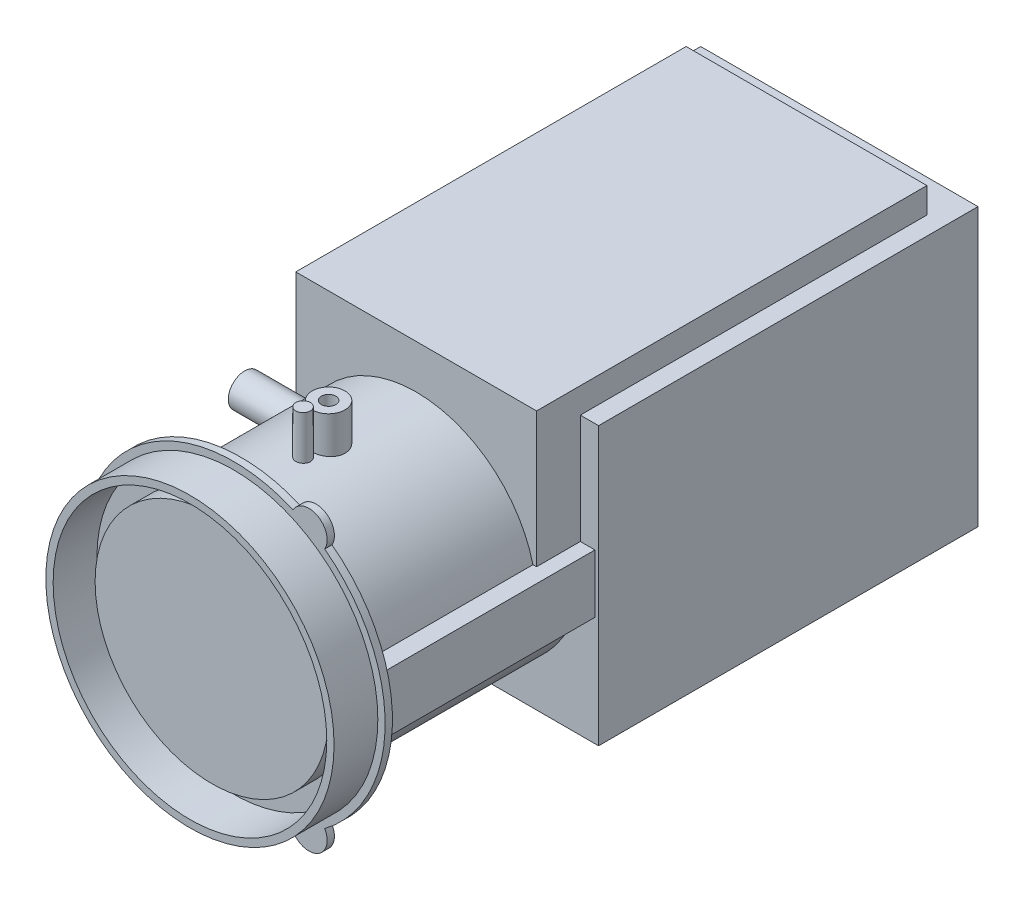
SolidWorks part; units mm, degrees
ref_plane "Front Plane" through (0, 0, 0) normal (0, 0, 1) x (1, 0, 0)
ref_plane "Top Plane" through (0, 0, 0) normal (0, 1, 0) x (1, 0, 0)
ref_plane "Right Plane" through (0, 0, 0) normal (1, 0, 0) x (0, 0, -1)
sketch "Sketch1" plane through (0, 0, 0) normal (0, 0, 1) x (1, 0, 0)
  circle A0 centre (0, 0) radius 19.75
  circle A1 centre (0, 0) radius 18.75
  dimension "D1" = 39.5
  dimension "D2" = 1
extrude "Boss-Extrude1" add sketch "Sketch1" along normal blind 6
sketch "Sketch2" plane through (0, 0, 0) normal (0, 0, -1) x (-1, 0, 0)
  arc A0 (-12.4645, 16.5891) -> (-12.4645, -16.5891) centre (0, 0) ccw
  arc A1 (20.5988, 2.5) -> (20.5988, -2.5) centre (20.5988, 0) cw
  arc A2 (-8.1344, -19.0891) -> (-12.4645, -16.5891) centre (-10.2994, -17.8391) cw
  arc A3 (-12.4645, 16.5891) -> (-8.1344, 19.0891) centre (-10.2994, 17.8391) cw
  arc A4 (20.5988, 2.5) -> (-8.1344, 19.0891) centre (0, 0) ccw
  arc A5 (-8.1344, -19.0891) -> (20.5988, -2.5) centre (0, 0) ccw
  point P7 (-14.3409, 19.3572)
  point P8 (-8.8874, 18.7504)
  point P14 (0, 0)
  point P15 (-12.1037, 16.8542)
  dimension "D1" = 41.5
  dimension "D2" = 2.5
  dimension "D3" = 3
extrude "Boss-Extrude2" add sketch "Sketch2" along normal blind 1
sketch "Sketch3" plane through (0, 0, -1) normal (0, 0, -1) x (-1, 0, 0)
  line L0 (16.0078, 4) -> (18.5, 4)
  line L1 (-18.5, 4) -> (-16.0078, 4)
  line L2 (-18.5, 4) -> (-18.5, -4)
  line L3 (-18.5, -4) -> (-16.0078, -4)
  line L4 (18.5, 4) -> (18.5, -4)
  line L5 (16.0078, -4) -> (18.5, -4)
  arc A0 (-16.0078, -4) -> (16.0078, -4) centre (0, 0) ccw
  arc A1 (16.0078, 4) -> (-16.0078, 4) centre (0, 0) ccw
  point P7 (24.1537, -6.3031)
  point P8 (-18.5, 0)
  dimension "D1" = 33
  dimension "D2" = 8
  dimension "D3" = 37
  dimension "D4" = 18.5
extrude "Boss-Extrude3" add sketch "Sketch3" along normal blind 70
sketch "Sketch4" plane through (0, 0, 0) normal (0, 1, 0) x (1, 0, 0)
  circle A0 centre (0, 13) radius 2.25
  circle A1 centre (0, 13) radius 1
  circle A2 centre (-3, 50.5) radius 2.25 construction
  circle A3 centre (-3, 50.5) radius 1 construction
  dimension "D1" = 4.5
  dimension "D3" = 2
  dimension "D4" = 4.5
  dimension "D2" = 13
  dimension "D5" = 37.5
  dimension "D6" = 3
extrude "Boss-Extrude4" add sketch "Sketch4" along normal mid plane 43
sketch "Sketch5" plane through (0, 0, 0) normal (0, 1, 0) x (1, 0, 0)
  circle A0 centre (0, 9.5) radius 1
  circle A1 centre (0, 13) radius 1 construction
  point P5 (0, 0)
  dimension "D1" = 2
  dimension "D2" = 3.5
extrude "Boss-Extrude5" add sketch "Sketch5" along normal mid plane 45
sketch "Sketch6" plane through (0, 0, 0) normal (0, 1, 0) x (1, 0, 0)
  circle A0 centre (3, 50.5) radius 2.25
  circle A1 centre (3, 50.5) radius 1
  circle A2 centre (0, 13) radius 1 construction
  circle A3 centre (0, 13) radius 1 construction
  dimension "D1" = 37.5
  dimension "D3" = 2
  dimension "D4" = 4.5
  dimension "D2" = 3
extrude "Boss-Extrude6" add sketch "Sketch6" against normal blind 21.5
sketch "Sketch7" plane through (0, 0, 0) normal (0, 1, 0) x (1, 0, 0)
  circle A0 centre (0.5, 54.5) radius 1
  circle A1 centre (3, 50.5) radius 1 construction
  dimension "D1" = 2
  dimension "D3" = 4
  dimension "D2" = 2.5
extrude "Boss-Extrude7" add sketch "Sketch7" against normal blind 22.5
sketch "Sketch8" plane through (0, 0, 0) normal (1, 0, 0) x (0, 0, -1)
  line L0 (1, -16.5) -> (1, -4) construction
  circle A0 centre (20, 0) radius 1
  point P5 (0, 0)
  dimension "D1" = 2
  dimension "D2" = 19
extrude "Boss-Extrude8" add sketch "Sketch8" against normal blind 20
sketch "Sketch9" plane through (0, 0, 0) normal (1, 0, 0) x (0, 0, -1)
  circle A0 centre (20, 10) radius 2.25
  circle A1 centre (20, 10) radius 1
  circle A2 centre (20, 0) radius 1 construction
  circle A3 centre (20, 0) radius 1 construction
  point P3 (0, 0)
  point P7 (0, 0)
  dimension "D1" = 2
  dimension "D2" = 4.5
  dimension "D3" = 10
extrude "Boss-Extrude9" add sketch "Sketch9" against normal blind 18.5
sketch "Sketch10" plane through (0, 0, 0) normal (0, 1, 0) x (1, 0, 0)
  line L1 (-16.5, 78.5) -> (16.5, 78.5)
  line L2 (-16.5, 78.5) -> (-16.5, 25)
  line L3 (-16.5, 25) -> (16.5, 25)
  line L4 (16.5, 78.5) -> (16.5, 25)
  point P4 (0, 25)
  dimension "D1" = 33
  dimension "D2" = 53.5
  dimension "D3" = 25
extrude "Boss-Extrude10" add sketch "Sketch10" along normal blind 22.5
sketch "Sketch11" plane through (0, 0, -71) normal (0, 0, -1) x (-1, 0, 0)
  line L1 (-19, 19) -> (19, 19)
  line L2 (-19, 19) -> (-19, -19)
  line L3 (-19, -19) -> (19, -19)
  line L4 (19, 19) -> (19, -19)
  line L5 (-19, 19) -> (19, -19) construction
  line L6 (-19, -19) -> (19, 19) construction
  point P0 (0, 0)
  dimension "D1" = 38
  dimension "D2" = 38
extrude "Boss-Extrude11" add sketch "Sketch11" along normal offset from surface 82 and the other way offset from surface (40 mm away) 30 up to face at (0, 0, -1) offset beyond the face yes other way up to face at (0, 0, -1)
sketch "Sketch12" plane through (0, 0, 0) normal (0, 0, 1) x (1, 0, 0)
  circle A0 centre (0, 0) radius 16
  dimension "D1" = 32
extrude "Boss-Extrude12" add sketch "Sketch12" along normal blind 3
